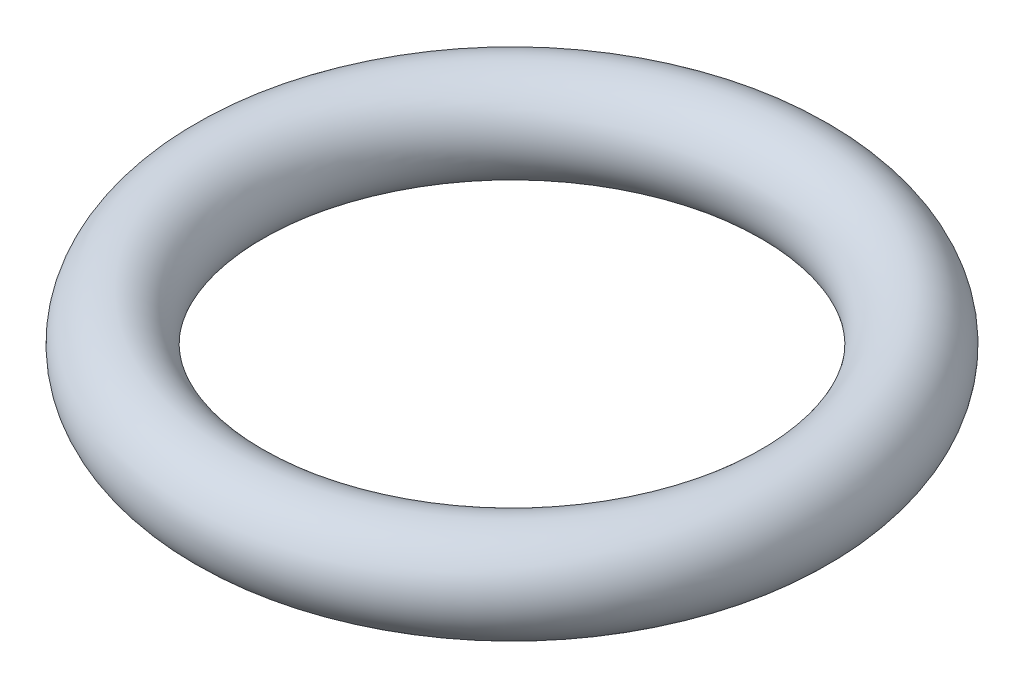
SolidWorks part; units mm, degrees
ref_plane "Front Plane" through (0, 0, 0) normal (0, 0, 1) x (1, 0, 0)
ref_plane "Top Plane" through (0, 0, 0) normal (0, 1, 0) x (1, 0, 0)
ref_plane "Right Plane" through (0, 0, 0) normal (1, 0, 0) x (0, 0, -1)
sketch "Sketch1" plane through (0, 0, 0) normal (0, 0, 1) x (1, 0, 0)
  line L0 (0, 0) -> (0, 51.0541) construction
  circle A0 centre (19.05, 0) radius 3.175
  dimension "D1" = 6.35
  dimension "D2" = 19.05
revolve "Revolve1" add sketch "Sketch1" angle 360 about L0
